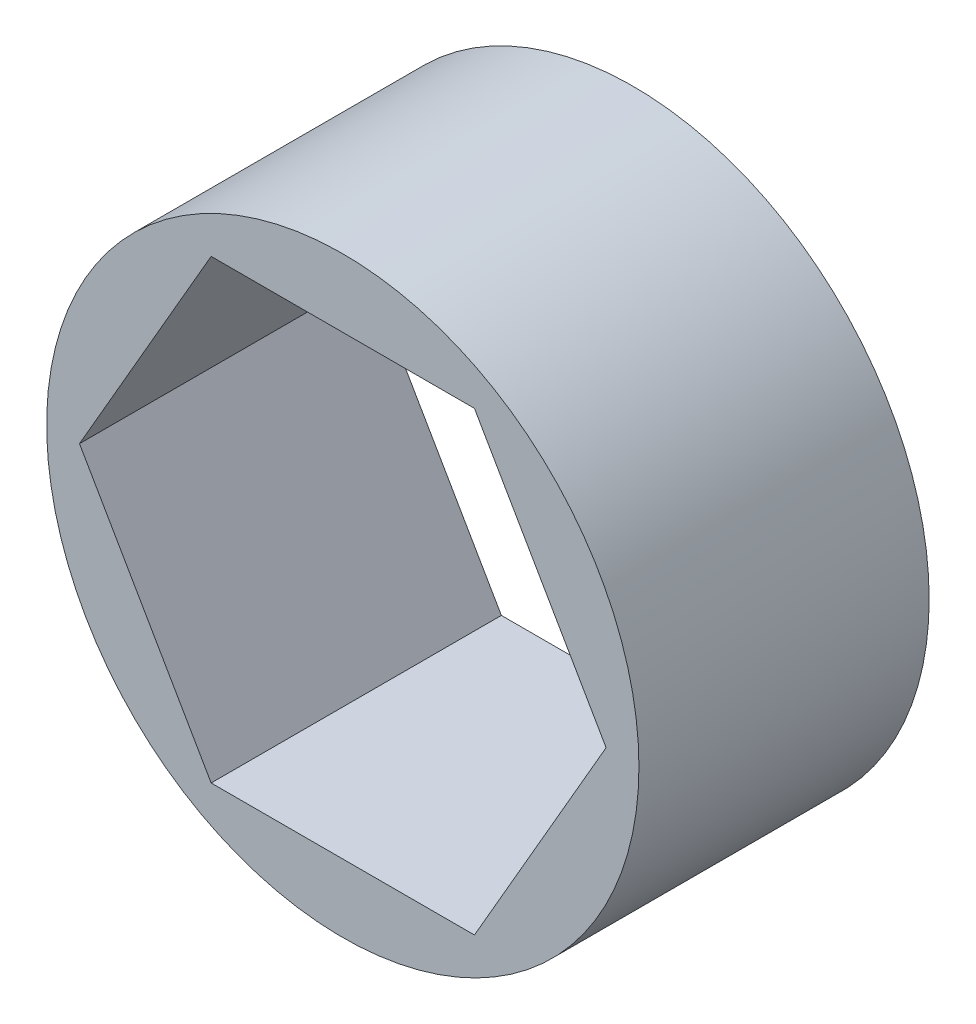
SolidWorks part; units mm, degrees
material "PET"
ref_plane "Front Plane" through (0, 0, 0) normal (0, 0, 1) x (1, 0, 0)
ref_plane "Top Plane" through (0, 0, 0) normal (0, 1, 0) x (1, 0, 0)
ref_plane "Right Plane" through (0, 0, 0) normal (1, 0, 0) x (0, 0, -1)
sketch "Sketch1" plane through (0, 0, 0) normal (0, 0, 1) x (1, 0, 0)
  line L1 (5.6459, 0) -> (2.823, 4.8895)
  line L2 (2.823, 4.8895) -> (-2.823, 4.8895)
  line L3 (-2.823, 4.8895) -> (-5.6459, 0)
  line L4 (-5.6459, 0) -> (-2.823, -4.8895)
  line L5 (-2.823, -4.8895) -> (2.823, -4.8895)
  line L6 (2.823, -4.8895) -> (5.6459, 0)
  circle A0 centre (0, 0) radius 4.8895 construction
  circle A1 centre (0, 0) radius 6.35
  dimension "D1" = 9.779
  dimension "D2" = 12.7
extrude "Boss-Extrude1" add sketch "Sketch1" along normal blind 6.223
